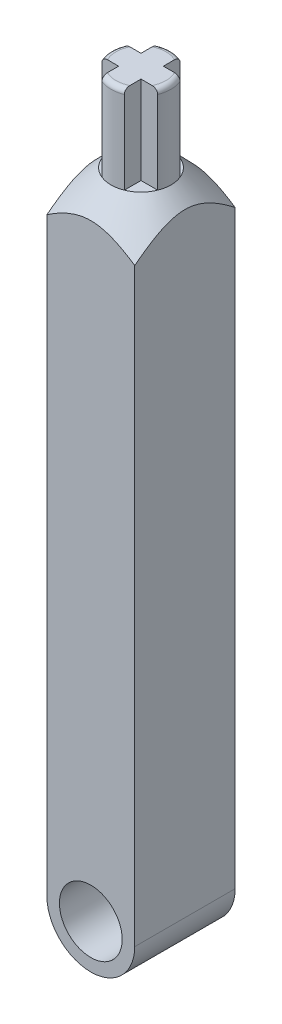
SolidWorks part; units mm, degrees
ref_plane "正面" through (0, 0, 0) normal (0, 0, 1) x (1, 0, 0)
ref_plane "平面" through (0, 0, 0) normal (0, 1, 0) x (1, 0, 0)
ref_plane "右側面" through (0, 0, 0) normal (1, 0, 0) x (0, 0, -1)
sketch "ｽｹｯﾁ1" plane through (0, 0, 0) normal (0, 0, 1) x (1, 0, 0)
  line L0 (-3.5, 0) -> (-3.5, 50)
  line L1 (3.5, 0) -> (3.5, 50)
  line L2 (-3.5, 50) -> (3.5, 50)
  arc A0 (-3.5, 0) -> (3.5, 0) centre (0, 0) ccw
  circle A1 centre (0, 0) radius 2.5
  dimension "D2" = 5
  dimension "D1" = 7
  dimension "D3" = 50
extrude "ﾎﾞｽ - 押し出し1" add sketch "ｽｹｯﾁ1" along normal blind 8
sketch "ｽｹｯﾁ2" plane through (0, 50, 0) normal (0, 1, 0) x (1, 0, 0)
  line L0 (-3.5, 0) -> (3.5, -8) construction
  line L1 (3.5, 0) -> (-3.5, -8) construction
  line L3 (-0.89, -1.7819) -> (-0.89, -3.11)
  line L4 (-0.89, -3.11) -> (-2.2181, -3.11)
  line L5 (0.89, -1.7819) -> (0.89, -3.11)
  line L6 (0.89, -3.11) -> (2.2181, -3.11)
  line L7 (-2.2181, -4.89) -> (-0.89, -4.89)
  line L8 (-0.89, -4.89) -> (-0.89, -6.2181)
  line L9 (2.2181, -4.89) -> (0.89, -4.89)
  line L10 (0.89, -4.89) -> (0.89, -6.2181)
  line L16 (2.39, -2.1501) -> (2.39, -5.2066) construction
  circle A0 centre (0, -4) radius 2.39 construction
  arc A1 (-0.89, -1.7819) -> (0.89, -1.7819) centre (0, -4) cw
  arc A2 (2.2181, -3.11) -> (2.2181, -4.89) centre (0, -4) cw
  arc A3 (-0.89, -6.2181) -> (0.89, -6.2181) centre (0, -4) ccw
  arc A4 (-2.2181, -3.11) -> (-2.2181, -4.89) centre (0, -4) ccw
  dimension "D2" = 4.78
  dimension "D1" = 1.5
ref_plane "平面1" through (-1.9823, 0, 1.7345) normal (-0.7526, 0, 0.6585) x (0.6585, 0, 0.7526)
extrude "ﾎﾞｽ - 押し出し3" add sketch "ｽｹｯﾁ2" along normal blind 7
fillet "ﾌｨﾚｯﾄ1" radius 0.4 4 edges at (0, 57, 6.39) (2.39, 57, 4) (0, 57, 1.61) (-2.39, 57, 4)
sketch "ｽｹｯﾁ5" plane through (-1.9823, 0, 1.7345) normal (-0.7526, 0, 0.6585) x (0.6585, 0, 0.7526)
  line L0 (0.6203, 50) -> (-2.3048, 47)
  line L1 (-2.3048, 50) -> (-2.3048, 0) construction
  line L2 (-2.3048, 47) -> (-2.3048, 50)
  line L3 (-2.3048, 50) -> (0.6203, 50)
  line L4 (3.7158, 50) -> (-2.3048, 50) construction
  line L5 (3.0103, 56.6) -> (3.0103, 50) construction
  dimension "D1" = 3
  dimension "D2" = 2.39
revolve "ｶｯﾄ - 回転2" cut sketch "ｽｹｯﾁ5" angle 360 about axis through (0, 57, 4) along (0, -1, 0)
